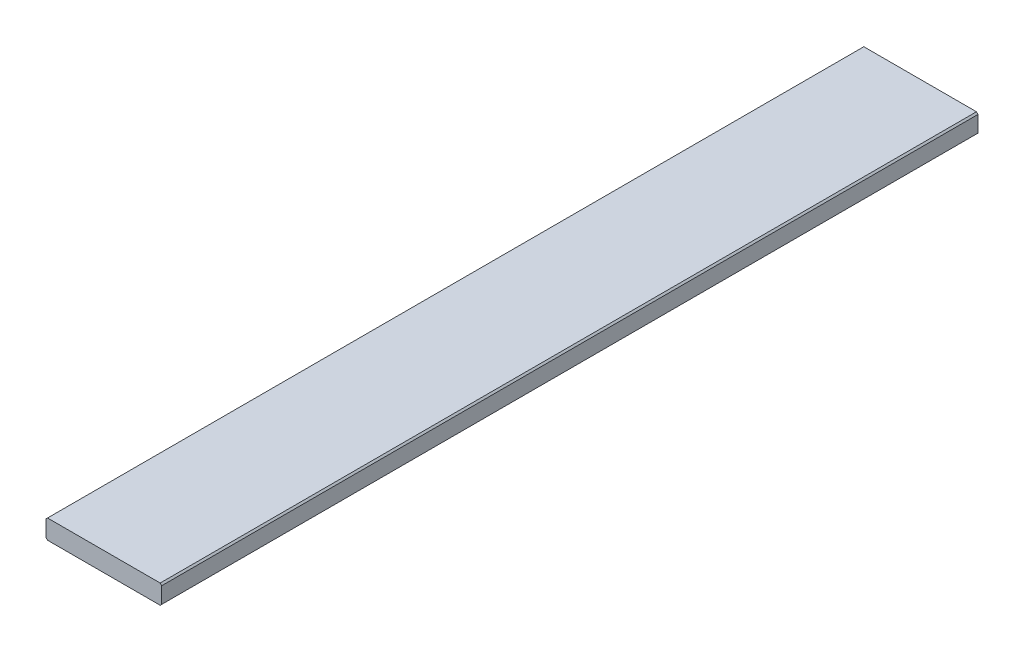
SolidWorks part; units mm, degrees
ref_plane "Спереди" through (0, 0, 0) normal (0, 0, 1) x (1, 0, 0)
ref_plane "Сверху" through (0, 0, 0) normal (0, 1, 0) x (1, 0, 0)
ref_plane "Справа" through (0, 0, 0) normal (1, 0, 0) x (0, 0, -1)
sketch "Эскиз1" plane through (0, 0, 0) normal (0, 0, 1) x (1, 0, 0)
  line L0 (-75, 10.5) -> (-73, 12.5)
  line L1 (-73, 12.5) -> (73, 12.5)
  line L2 (-75, 10.5) -> (-75, -10.5)
  line L3 (-73, -12.5) -> (73, -12.5)
  line L4 (75, 10.5) -> (75, -10.5)
  line L5 (-75, 12.5) -> (75, -12.5) construction
  line L6 (-75, -12.5) -> (75, 12.5) construction
  line L7 (-75, -10.5) -> (-73, -12.5)
  line L8 (73, -12.5) -> (75, -10.5)
  line L9 (73, 12.5) -> (75, 10.5)
  point P0 (0, 0)
  dimension "D1" = 150
  dimension "D2" = 25
extrude "Бобышка-Вытянуть1" add sketch "Эскиз1" along normal blind 1058
